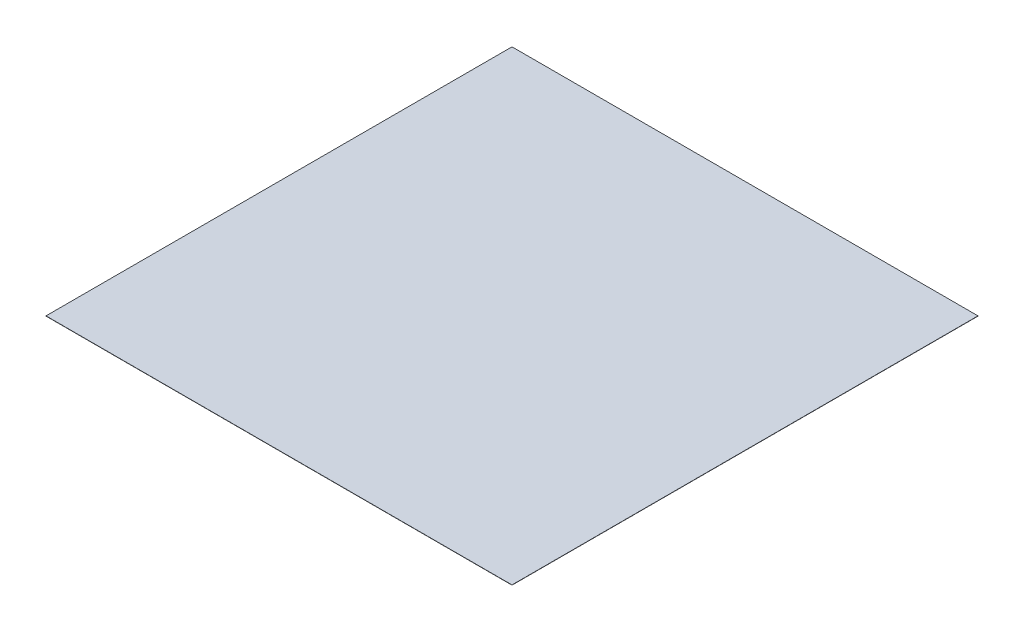
SolidWorks part; units mm, degrees
material "AISI 1020"
ref_plane "Front" through (0, 0, 0) normal (0, 0, 1) x (1, 0, 0)
ref_plane "Top" through (0, 0, 0) normal (0, 1, 0) x (1, 0, 0)
ref_plane "Right" through (0, 0, 0) normal (1, 0, 0) x (0, 0, -1)
sketch "Эскиз1" plane through (0, 0, 0) normal (0, 1, 0) x (1, 0, 0)
  line L1 (-2000, -2000) -> (2000, -2000)
  line L2 (-2000, -2000) -> (-2000, 2000)
  line L3 (-2000, 2000) -> (2000, 2000)
  line L4 (2000, -2000) -> (2000, 2000)
  line L5 (-2000, -2000) -> (2000, 2000) construction
  line L6 (-2000, 2000) -> (2000, -2000) construction
  point P0 (0, 0)
  dimension "D1" = 4000
  dimension "D2" = 4000
extrude "Бобышка-Вытянуть1" add sketch "Эскиз1" along normal blind 2
